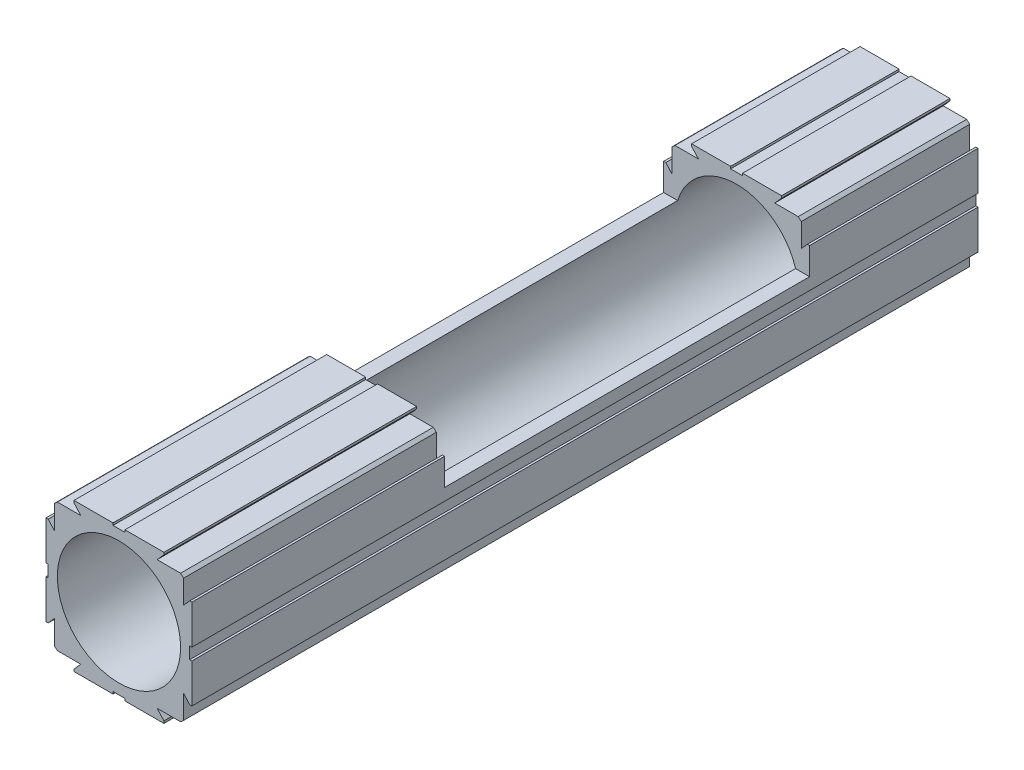
SolidWorks part; units mm, degrees
ref_plane "Front Plane" through (0, 0, 0) normal (0, 0, 1) x (1, 0, 0)
ref_plane "Top Plane" through (0, 0, 0) normal (0, 1, 0) x (1, 0, 0)
ref_plane "Right Plane" through (0, 0, 0) normal (1, 0, 0) x (0, 0, -1)
sketch "Sketch2" plane through (0, 0, 0) normal (0, 0, 1) x (1, 0, 0)
  line L0 (-20.338, 33.5291) -> (-2.6993, 33.5291)
  line L1 (-2.6993, 33.5291) -> (-2.6993, 32.5352)
  line L2 (-2.6993, 32.5352) -> (2.6993, 32.5352)
  line L3 (-20.338, 33.5291) -> (-20.338, 32.5352)
  line L4 (-20.338, 32.5352) -> (-17.2715, 29.113)
  line L5 (-17.2715, 29.113) -> (-27.8712, 29.113)
  line L6 (-27.8712, 29.113) -> (-29.2621, 27.8667)
  line L7 (-29.2621, 27.8667) -> (-29.2621, 17.267)
  line L8 (-29.2621, 17.267) -> (-32.0139, 20.338)
  line L9 (-32.0139, 20.338) -> (-33.0078, 20.338)
  line L10 (-33.0078, 20.338) -> (-33.0078, 2.6993)
  line L11 (-33.0078, 2.6993) -> (-32.0139, 2.6993)
  line L12 (-32.0139, 2.6993) -> (-32.0139, -2.6993)
  line L13 (-32.0139, 0) -> (0, 0) construction
  line L14 (0, 0) -> (0, 32.5352) construction
  line L15 (32.0139, 2.6993) -> (32.0139, -2.6993)
  line L16 (33.0078, 2.6993) -> (32.0139, 2.6993)
  line L17 (33.0078, 20.338) -> (33.0078, 2.6993)
  line L18 (32.0139, 20.338) -> (33.0078, 20.338)
  line L19 (29.2621, 17.267) -> (32.0139, 20.338)
  line L20 (29.2621, 27.8667) -> (29.2621, 17.267)
  line L21 (27.8712, 29.113) -> (29.2621, 27.8667)
  line L22 (17.2715, 29.113) -> (27.8712, 29.113)
  line L23 (20.338, 32.5352) -> (17.2715, 29.113)
  line L24 (20.338, 33.5291) -> (20.338, 32.5352)
  line L25 (2.6993, 33.5291) -> (2.6993, 32.5352)
  line L26 (20.338, 33.5291) -> (2.6993, 33.5291)
  line L27 (20.338, -33.5291) -> (2.6993, -33.5291)
  line L28 (2.6993, -33.5291) -> (2.6993, -32.5352)
  line L29 (20.338, -33.5291) -> (20.338, -32.5352)
  line L30 (20.338, -32.5352) -> (17.2715, -29.113)
  line L31 (17.2715, -29.113) -> (27.8712, -29.113)
  line L32 (27.8712, -29.113) -> (29.2621, -27.8667)
  line L33 (29.2621, -27.8667) -> (29.2621, -17.267)
  line L34 (29.2621, -17.267) -> (32.0139, -20.338)
  line L35 (32.0139, -20.338) -> (33.0078, -20.338)
  line L36 (33.0078, -20.338) -> (33.0078, -2.6993)
  line L37 (33.0078, -2.6993) -> (32.0139, -2.6993)
  line L38 (-33.0078, -2.6993) -> (-32.0139, -2.6993)
  line L39 (-33.0078, -20.338) -> (-33.0078, -2.6993)
  line L40 (-32.0139, -20.338) -> (-33.0078, -20.338)
  line L41 (-29.2621, -17.267) -> (-32.0139, -20.338)
  line L42 (-29.2621, -27.8667) -> (-29.2621, -17.267)
  line L43 (-27.8712, -29.113) -> (-29.2621, -27.8667)
  line L44 (-17.2715, -29.113) -> (-27.8712, -29.113)
  line L45 (-20.338, -32.5352) -> (-17.2715, -29.113)
  line L46 (-20.338, -33.5291) -> (-20.338, -32.5352)
  line L47 (-2.6993, -32.5352) -> (2.6993, -32.5352)
  line L48 (-2.6993, -33.5291) -> (-2.6993, -32.5352)
  line L49 (-20.338, -33.5291) -> (-2.6993, -33.5291)
  circle A0 centre (0, 0) radius 27.8739
  point P40 (32.0139, 0)
  dimension "D5" = 41.862
extrude "Boss-Extrude1" add sketch "Sketch2" along normal blind 500
sketch "Sketch3" plane through (29.2621, 0, 0) normal (1, 0, 0) x (0, 0, -1)
  line L0 (-500, 33.5291) -> (0, 33.5291) construction
  line L1 (-385.7, 33.5291) -> (-220.6, 33.5291)
  line L2 (-385.7, 33.5291) -> (-385.7, 8.1291)
  line L3 (-385.7, 8.1291) -> (-220.6, 8.1291)
  line L4 (-220.6, 33.5291) -> (-220.6, 8.1291)
  line L5 (-500, 17.267) -> (-500, 27.8667) construction
  line L6 (-500, -33.5291) -> (0, -33.5291) construction
  line L7 (-144.4, 33.5291) -> (0, 33.5291)
  line L8 (-144.4, 33.5291) -> (-144.4, -33.5291)
  line L9 (-144.4, -33.5291) -> (0, -33.5291)
  line L10 (0, 33.5291) -> (0, -33.5291)
  line L11 (-500, -20.338) -> (-500, -2.6993) construction
  dimension "D1" = 25.4
  dimension "D2" = 114.3
  dimension "D3" = 165.1
  dimension "D4" = 355.6
extrude "Cut-Extrude1" cut sketch "Sketch3" against normal through all both and the other way through all
